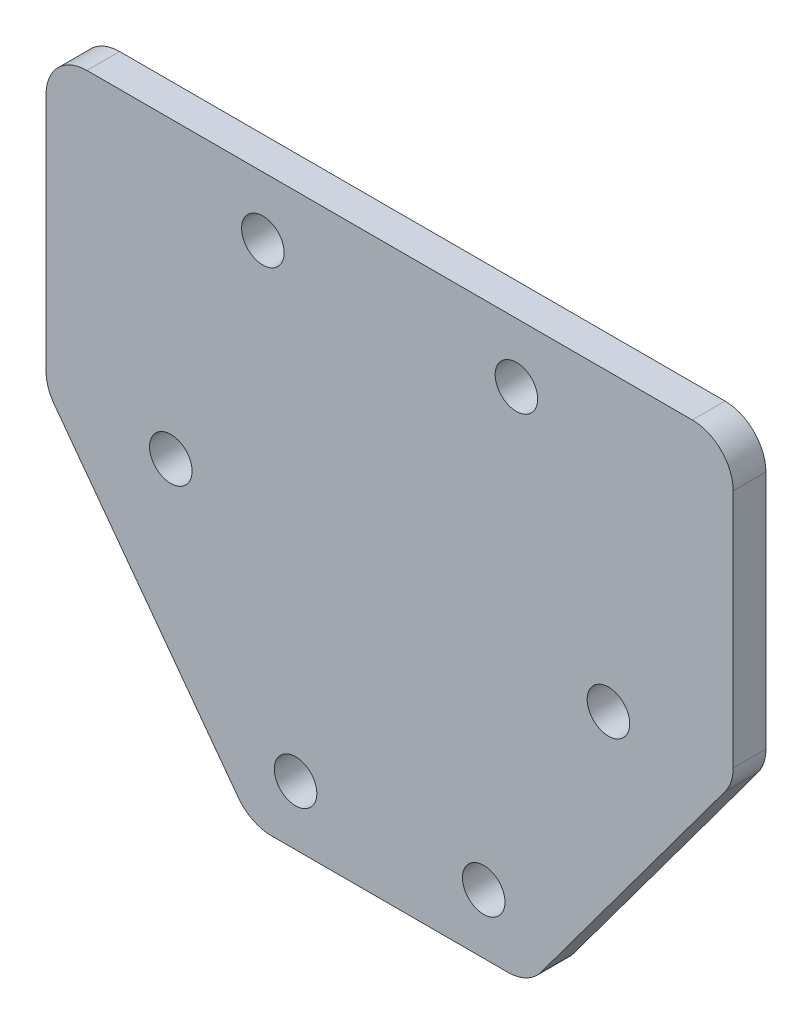
SolidWorks part; units mm, degrees
material "1060 Alloy"
ref_plane "Front Plane" through (0, 0, 0) normal (0, 0, 1) x (1, 0, 0)
ref_plane "Top Plane" through (0, 0, 0) normal (0, 1, 0) x (1, 0, 0)
ref_plane "Right Plane" through (0, 0, 0) normal (1, 0, 0) x (0, 0, -1)
sketch "Sketch1" plane through (0, 0, 0) normal (0, 0, 1) x (1, 0, 0)
  line L0 (-17, -51.7491) -> (17, -51.7491)
  line L1 (-42, 18) -> (42, 18)
  line L2 (-42, 18) -> (-42, -18)
  line L3 (-42, -18) -> (42, -18) construction
  line L4 (42, 18) -> (42, -18)
  line L5 (0, -18) -> (0, 18) construction
  line L6 (-42, 0) -> (42, 0) construction
  line L7 (-42, -18) -> (-17, -51.7491)
  line L8 (17, -51.7491) -> (42, -18)
  circle A0 centre (-15.5, 10.75) radius 2.6
  circle A1 centre (15.5, 10.75) radius 2.6
  circle A2 centre (-26.75, -18) radius 2.6
  circle A3 centre (26.75, -18) radius 2.6
  circle A4 centre (-11.5, -44.4991) radius 2.6
  circle A5 centre (11.5, -44.4991) radius 2.6
  point P0 (0, 0)
  point P7 (0, -51.7491)
  dimension "D5" = 5.2
  dimension "D6" = 7.25
  dimension "D7" = 31
  dimension "D9" = 53.5
  dimension "D10" = 26.75
  dimension "D11" = 23
  dimension "D12" = 11.5
  dimension "D13" = 7.25
  dimension "D1" = 84
  dimension "D2" = 36
  dimension "D3" = 34
  dimension "D4" = 42
extrude "Boss-Extrude1" add sketch "Sketch1" along normal blind 4
fillet "Fillet1" radius 5 6 edges at (17, -51.7491, 2) (-42, -18, 2) (-42, 18, 2) (42, 18, 2) (42, -18, 2) (-17, -51.7491, 2)
